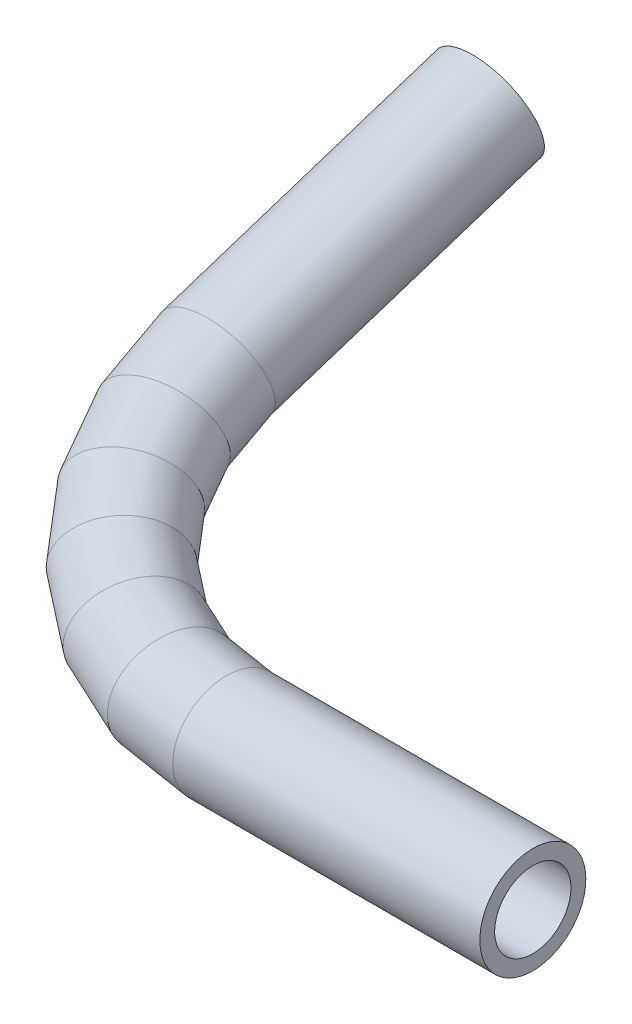
SolidWorks part; units mm, degrees
ref_plane "Front Plane" through (0, 0, 0) normal (0, 0, 1) x (1, 0, 0)
ref_plane "Top Plane" through (0, 0, 0) normal (0, 1, 0) x (1, 0, 0)
ref_plane "Right Plane" through (0, 0, 0) normal (1, 0, 0) x (0, 0, -1)
sketch3d "Path"
  line L0 (-2754.8928, 10.1976, -31.3849) -> (-2773.0928, 10.1976, -31.3849)
  line L1 (-2773.0928, 10.1976, -31.3849) -> (-2776.9751, 10.3555, -31.871)
  line L2 (-2776.9751, 10.3555, -31.871) -> (-2780.5928, 10.8186, -33.2961)
  line L3 (-2780.5928, 10.8186, -33.2961) -> (-2783.6994, 11.5552, -35.5632)
  line L4 (-2783.6994, 11.5552, -35.5632) -> (-2786.0832, 12.5152, -38.5178)
  line L5 (-2786.0832, 12.5152, -38.5178) -> (-2787.5817, 13.6331, -41.9584)
  line L6 (-2787.5817, 13.6331, -41.9584) -> (-2788.0928, 14.8328, -45.6507)
  line L7 (-2788.0928, 14.8328, -45.6507) -> (-2788.0928, 20.1325, -61.9613)
ref_plane "Start Plane" through (-2754.8928, 0, 0) normal (1, 0, 0) x (0, 0, -1)
sketch "Profile" plane through (-2754.8928, 0, 0) normal (1, 0, 0) x (0, 0, -1)
  circle A0 centre (31.3849, 10.1976) radius 3.175
  circle A1 centre (31.3849, 10.1976) radius 2.286
sweep "Tube" add profiles "Profile" path "Path"
